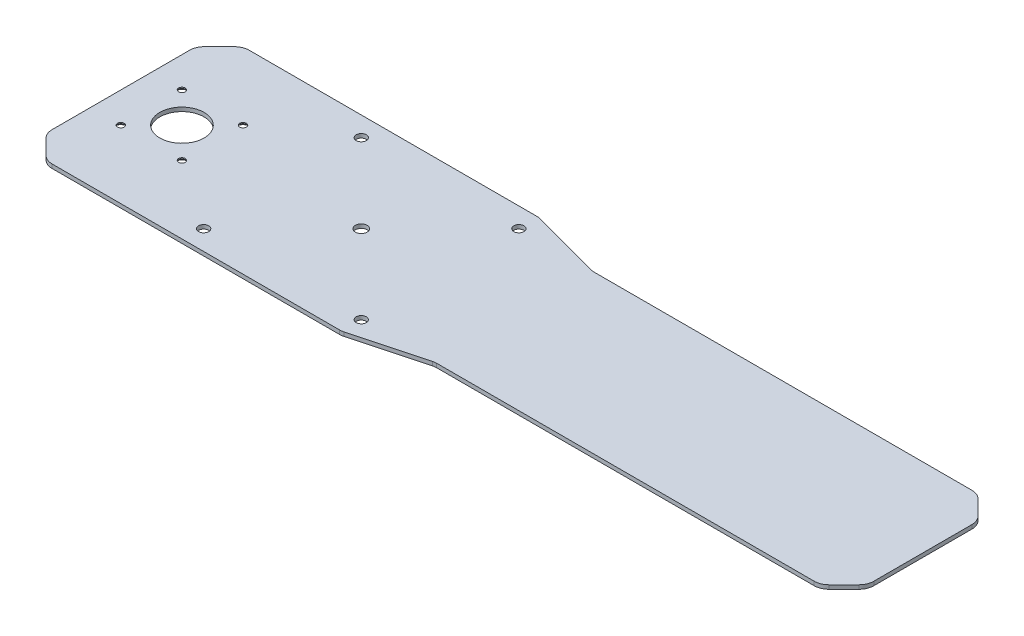
SolidWorks part; units mm, degrees
material "1060 Alloy"
ref_plane "Front Plane" through (0, 0, 0) normal (0, 0, 1) x (1, 0, 0)
ref_plane "Top Plane" through (0, 0, 0) normal (0, 1, 0) x (1, 0, 0)
ref_plane "Right Plane" through (0, 0, 0) normal (1, 0, 0) x (0, 0, -1)
sketch "Sketch1" plane through (0, 0, 0) normal (0, 1, 0) x (1, 0, 0)
  line L0 (40, -50) -> (77.3205, -40)
  line L1 (-40, 50) -> (40, 50)
  line L2 (-40, 50) -> (-40, -50) construction
  line L3 (-40, -50) -> (40, -50)
  line L4 (40, 50) -> (40, -50) construction
  line L5 (-40, 50) -> (40, -50) construction
  line L6 (-40, -50) -> (40, 50) construction
  line L7 (-40, 50) -> (-122, 50)
  line L8 (-40, 50) -> (-40, -50) construction
  line L9 (-40, -50) -> (-122, -50)
  line L10 (-122, 50) -> (-122, -50)
  line L12 (40, 50) -> (40, -50) construction
  line L14 (40, 50) -> (77.3205, 40)
  line L16 (77.3205, 40) -> (285, 40)
  line L17 (77.3205, 40) -> (77.3205, -40) construction
  line L18 (77.3205, -40) -> (285, -40)
  line L19 (285, 40) -> (285, -40)
  point P0 (0, 0)
  point P11 (250, 0)
  dimension "D1" = 80
  dimension "D2" = 100
  dimension "D5" = 250
  dimension "D4" = 75
  dimension "D6" = 75
  dimension "D7" = 80
  dimension "D8" = 35
  dimension "D3" = 82
extrude "Boss-Extrude2" add sketch "Sketch1" along normal blind 2
chamfer "Chamfer2" distance 12 angle 45 4 edges at (-122, 1, 50) (-122, 1, -50) (285, 1, -40) (285, 1, 40)
fillet "Fillet1" radius 7.5 12 edges at (-110, 1, -50) (-122, 1, -38) (-122, 1, 38) (-110, 1, 50) (273, 1, 40) (285, 1, 28) (285, 1, -28) (273, 1, -40) (40, 1, 50) (77.3205, 1, 40) (77.3205, 1, -40) (40, 1, -50)
sketch "Sketch2" plane through (0, 2, 0) normal (0, 1, 0) x (1, 0, 0)
  line L0 (0, 50) -> (0, -50) construction
  line L1 (39.0126, 50) -> (-106.8934, 50) construction
  line L2 (-106.8934, -50) -> (39.0126, -50) construction
  line L3 (-122, 0) -> (285, 0) construction
  line L4 (-122, 34.8934) -> (-122, -34.8934) construction
  line L5 (285, -24.8934) -> (285, 24.8934) construction
  circle A0 centre (-40, 40) radius 2.575
  circle A1 centre (40, 40) radius 2.575
  circle A2 centre (40, -40) radius 2.575
  circle A3 centre (-40, -40) radius 2.575
  circle A4 centre (-91, 0) radius 11.25
  circle A5 centre (0, 0) radius 3
  dimension "D3" = 5.15
  dimension "D4" = 22.5
  dimension "D6" = 6
  dimension "D1" = 40
  dimension "D2" = 40
  dimension "D5" = 31
extrude "Cut-Extrude1" cut sketch "Sketch2" against normal through all
hole_wizard "CSK for M3 Countersunk Flat Head Screw2" positions "Sketch5" profile "Sketch4" countersink size "M3" standard "DIN" end condition through all
sketch "Sketch5" plane through (0, 0, 0) normal (0, -1, 0) x (-1, 0, 0)
  line L0 (122, 0) -> (0, 0) construction
  line L1 (122, 34.8934) -> (122, -34.8934) construction
  line L3 (91, -50) -> (91, 50) construction
  line L4 (106.8934, -50) -> (-39.0126, -50) construction
  line L5 (-39.0126, 50) -> (106.8934, 50) construction
  point P16 (106.5, -15.5)
  point P22 (75.5, -15.5)
  point P23 (75.5, 15.5)
  point P24 (106.5, 15.5)
  dimension "D5" = 31
  dimension "D3" = 15.5
  dimension "D7" = 31
  dimension "D6" = 31
  dimension "D4" = 15.5
  dimension "D1" = 2
  dimension "D2" = 2
sketch "Sketch4" plane through (-106.5, 0, -15.5) normal (1, 0, 0) x (0, 0, -1)
  line L0 (0, 0) -> (0, 2)
  line L1 (0, 2) -> (1.7, 2)
  line L2 (1.7, 2) -> (1.7, 1.45)
  line L3 (1.7, 1.45) -> (3.15, 0)
  line L5 (3.15, 0) -> (0, 0)
  line L6 (-1.7, 1.45) -> (-3.15, 0) construction
  line L11 (0, -6.35) -> (0, 107.95) construction
  dimension "Thru Hole Dia." = 3.4
  dimension "Thru Hole Depth" = 2
  dimension "Near C'Sink Dia." = 6.3
  dimension "Near C'Sink Angle" = 90
equation "\"Elevator Guide Rod Distance\"= 80mm"
equation "\"Extra Spacing\"= 20mm"
equation "\"Plate Thickness\"= 2mm"
equation "\"D1@Sketch1\"=\"Elevator Guide Rod Distance\""
equation "\"D2@Sketch1\"=\"Elevator Guide Rod Distance\"+\"Extra Spacing\""
equation "\"Elevator Servo Offset\"= 75mm"
equation "\"Servo Width\"= 42mm"
equation "\"Pivot Point End Offset\"= 35mm"
equation "\"Origin Pivot Distance\"= 250mm"
equation "\"D5@Sketch1\"=\"Origin Pivot Distance\""
equation "\"Narrow Section Width\"= 80mm"
equation "\"D7@Sketch1\"=\"Narrow Section Width\""
equation "\"D8@Sketch1\"=\"Pivot Point End Offset\""
equation "\"D1@Sketch2\"=\"Elevator Guide Rod Distance\"/2"
equation "\"D2@Sketch2\"=\"Elevator Guide Rod Distance\"/2"
equation "\"Guide Rod Diameter\"= 5mm"
equation "\"D3@Sketch2\"=\"Guide Rod Diameter\"+.15"
equation "\"Servo Hole X-Offset\"= 15.5mm"
equation "\"Servo Hole Y-Offset\"= 15.5mm"
equation "\"D1\"= \"Servo Width\" / 2 + \"Extra Spacing\""
equation "\"D3@Sketch5\"=\"Servo Hole Y-Offset\""
equation "\"D5@Sketch5\"= \"Servo Width\" / 2 + \"Extra Spacing\" / 2"
equation "\"D7@Sketch5\"=\"Servo Hole Y-Offset\"*2"
equation "\"D6@Sketch5\"=\"Servo Hole X-Offset\"*2 "
equation "\"D4@Sketch5\"=\"Servo Hole X-Offset\""
equation "\"Servo Shaft Diameter\"= 22.5mm"
equation "\"D5@Sketch2\"= \"Servo Width\" / 2 + \"Extra Spacing\" / 2"
equation "\"D4@Sketch2\"=\"Servo Shaft Diameter\""
equation "\"Elevator Screw Lift Diameter\"= 6mm"
equation "\"D6@Sketch2\"=\"Elevator Screw Lift Diameter\""
equation "\"D3@Sketch1\"= \"Servo Width\" + \"Extra Spacing\" * 2"
equation "\"D1@Boss-Extrude2\"=\"Plate Thickness\""
